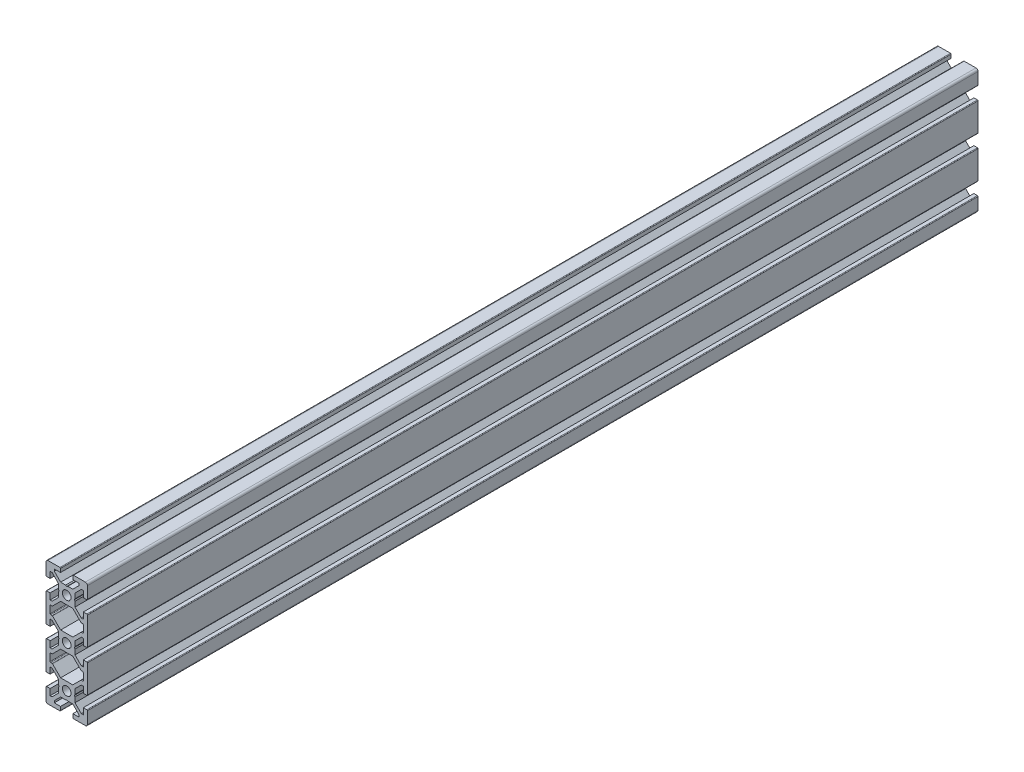
SolidWorks part; units mm, degrees
ref_plane "Front Plane" through (0, 0, 0) normal (0, 0, 1) x (1, 0, 0)
ref_plane "Top Plane" through (0, 0, 0) normal (0, 1, 0) x (1, 0, 0)
ref_plane "Right Plane" through (0, 0, 0) normal (1, 0, 0) x (0, 0, -1)
ref_plane "Plane1" through (0, 0, 0) normal (0, 0, 1) x (1, 0, 0)
sketch "Sketch1" plane through (0, 0, 0) normal (0, 0, 1) x (1, 0, 0)
  line L0 (-10, 16.7) -> (-10, 3.3)
  line L1 (-9.7, 3) -> (-8, 3)
  line L2 (-8, 3) -> (-8, 6)
  line L3 (-8, 6) -> (-7.0607, 6)
  line L4 (-7.0607, 6) -> (-4, 2.9393)
  line L5 (-4, 2.9393) -> (-4, 0.5196)
  line L6 (-4, 0.5196) -> (-3.7, 0)
  line L7 (-3.7, 0) -> (-4, -0.5196)
  line L8 (-4, -0.5196) -> (-4, -2.9394)
  line L9 (-4, -2.9394) -> (-7.0606, -6)
  line L10 (-7.0606, -6) -> (-8, -6)
  line L11 (-8, -6) -> (-8, -3)
  line L12 (-8, -3) -> (-9.7, -3)
  line L13 (-10, -3.3) -> (-10, -16.7)
  line L14 (-9.7, -17) -> (-8, -17)
  line L15 (-8, -17) -> (-8, -14)
  line L16 (-8, -14) -> (-7.0607, -14)
  line L17 (-7.0607, -14) -> (-4, -17.0607)
  line L18 (-4, -17.0607) -> (-4, -19.4804)
  line L19 (-4, -19.4804) -> (-3.7, -20)
  line L20 (-3.7, -20) -> (-4, -20.5196)
  line L21 (-4, -20.5196) -> (-4, -22.9394)
  line L22 (-4, -22.9394) -> (-7.0606, -26)
  line L23 (-7.0606, -26) -> (-8, -26)
  line L24 (-8, -26) -> (-8, -23)
  line L25 (-8, -23) -> (-9.7, -23)
  line L26 (-10, -23.3) -> (-10, -29)
  line L27 (-9, -30) -> (-3.3, -30)
  line L28 (-3, -29.7) -> (-3, -28)
  line L29 (-3, -28) -> (-6, -28)
  line L30 (-6, -28) -> (-6, -27.0607)
  line L31 (-6, -27.0607) -> (-2.9393, -24)
  line L32 (-2.9393, -24) -> (-0.5191, -24)
  line L33 (-0.5191, -24) -> (0, -23.7)
  line L34 (0, -23.7) -> (0.5186, -24)
  line L35 (0.5186, -24) -> (2.9393, -24)
  line L36 (2.9393, -24) -> (6, -27.0607)
  line L37 (6, -27.0607) -> (6, -28)
  line L38 (6, -28) -> (3, -28)
  line L39 (3, -28) -> (3, -29.7)
  line L40 (3.3, -30) -> (9, -30)
  line L41 (10, -29) -> (10, -23.3)
  line L42 (9.7, -23) -> (8, -23)
  line L43 (8, -23) -> (8, -26)
  line L44 (8, -26) -> (7.0606, -26)
  line L45 (7.0606, -26) -> (4, -22.9394)
  line L46 (4, -22.9394) -> (4, -20.5196)
  line L47 (4, -20.5196) -> (3.7, -20)
  line L48 (3.7, -20) -> (4, -19.4804)
  line L49 (4, -19.4804) -> (4, -17.0607)
  line L50 (4, -17.0607) -> (7.0607, -14)
  line L51 (7.0607, -14) -> (8, -14)
  line L52 (8, -14) -> (8, -17)
  line L53 (8, -17) -> (9.7, -17)
  line L54 (10, -16.7) -> (10, -3.3)
  line L55 (9.7, -3) -> (8, -3)
  line L56 (8, -3) -> (8, -6)
  line L57 (8, -6) -> (7.0607, -6)
  line L58 (7.0607, -6) -> (4, -2.9393)
  line L59 (4, -2.9393) -> (4, -0.5196)
  line L60 (4, -0.5196) -> (3.7, 0)
  line L61 (3.7, 0) -> (4, 0.5196)
  line L62 (4, 0.5196) -> (4, 2.9393)
  line L63 (4, 2.9393) -> (7.0607, 6)
  line L64 (7.0607, 6) -> (8, 6)
  line L65 (8, 6) -> (8, 3)
  line L66 (8, 3) -> (9.7, 3)
  line L67 (10, 3.3) -> (10, 16.7)
  line L68 (9.7, 17) -> (8, 17)
  line L69 (8, 17) -> (8, 14)
  line L70 (8, 14) -> (7.0607, 14)
  line L71 (7.0607, 14) -> (4, 17.0607)
  line L72 (4, 17.0607) -> (4, 19.4804)
  line L73 (4, 19.4804) -> (3.7, 20)
  line L74 (3.7, 20) -> (4, 20.5196)
  line L75 (4, 20.5196) -> (4, 22.9394)
  line L76 (4, 22.9394) -> (7.0606, 26)
  line L77 (7.0606, 26) -> (8, 26)
  line L78 (8, 26) -> (8, 23)
  line L79 (8, 23) -> (9.7, 23)
  line L80 (10, 23.3) -> (10, 29)
  line L81 (9, 30) -> (3.3, 30)
  line L82 (3, 29.7) -> (3, 28)
  line L83 (3, 28) -> (6, 28)
  line L84 (6, 28) -> (6, 27.0607)
  line L85 (6, 27.0607) -> (2.9393, 24)
  line L86 (2.9393, 24) -> (0.5196, 24)
  line L87 (0.5196, 24) -> (0, 23.7)
  line L88 (0, 23.7) -> (-0.5196, 24)
  line L89 (-0.5196, 24) -> (-2.9393, 24)
  line L90 (-2.9393, 24) -> (-6, 27.0607)
  line L91 (-6, 27.0607) -> (-6, 28)
  line L92 (-6, 28) -> (-3, 28)
  line L93 (-3, 28) -> (-3, 29.7)
  line L94 (-3.3, 30) -> (-9, 30)
  line L95 (-10, 29) -> (-10, 23.3)
  line L96 (-9.7, 23) -> (-8, 23)
  line L97 (-8, 23) -> (-8, 26)
  line L98 (-8, 26) -> (-7.0606, 26)
  line L99 (-7.0606, 26) -> (-4, 22.9394)
  line L100 (-4, 22.9394) -> (-4, 20.5196)
  line L101 (-4, 20.5196) -> (-3.7, 20)
  line L102 (-3.7, 20) -> (-4, 19.4804)
  line L103 (-4, 19.4804) -> (-4, 17.0607)
  line L104 (-4, 17.0607) -> (-7.0607, 14)
  line L105 (-7.0607, 14) -> (-8, 14)
  line L106 (-8, 14) -> (-8, 17)
  line L107 (-8, 17) -> (-9.7, 17)
  line L108 (-7.7, 8) -> (-7.0636, 8)
  line L109 (-6.8515, 7.9121) -> (-2.9393, 4)
  line L110 (-2.9393, 4) -> (2.9393, 4)
  line L111 (2.9393, 4) -> (6.8515, 7.9121)
  line L112 (7.0636, 8) -> (7.7, 8)
  line L113 (8, 8.3) -> (8, 11.7)
  line L114 (7.7, 12) -> (7.0636, 12)
  line L115 (6.8515, 12.0879) -> (2.9393, 16)
  line L116 (2.9393, 16) -> (-2.9393, 16)
  line L117 (-2.9393, 16) -> (-6.8515, 12.0879)
  line L118 (-7.0636, 12) -> (-7.7, 12)
  line L119 (-8, 11.7) -> (-8, 8.3)
  line L120 (-8, -8.3) -> (-8, -11.7)
  line L121 (-7.7, -12) -> (-7.0636, -12)
  line L122 (-6.8515, -12.0879) -> (-2.9394, -16)
  line L123 (-2.9394, -16) -> (2.9393, -16)
  line L124 (2.9393, -16) -> (6.8515, -12.0879)
  line L125 (7.0636, -12) -> (7.7, -12)
  line L126 (8, -11.7) -> (8, -8.3)
  line L127 (7.7, -8) -> (7.0636, -8)
  line L128 (6.8515, -7.9121) -> (2.9393, -4)
  line L129 (2.9393, -4) -> (-2.9393, -4)
  line L130 (-2.9393, -4) -> (-6.8515, -7.9121)
  line L131 (-7.0636, -8) -> (-7.7, -8)
  arc A0 (-10, 3.3) -> (-9.7, 3) centre (-9.7, 3.3) ccw
  arc A1 (-9.7, -3) -> (-10, -3.3) centre (-9.7, -3.3) ccw
  arc A2 (-10, -16.7) -> (-9.7, -17) centre (-9.7, -16.7) ccw
  arc A3 (-9.7, -23) -> (-10, -23.3) centre (-9.7, -23.3) ccw
  arc A4 (-10, -29) -> (-9, -30) centre (-9, -29) ccw
  arc A5 (-3.3, -30) -> (-3, -29.7) centre (-3.3, -29.7) ccw
  arc A6 (3, -29.7) -> (3.3, -30) centre (3.3, -29.7) ccw
  arc A7 (9, -30) -> (10, -29) centre (9, -29) ccw
  arc A8 (10, -23.3) -> (9.7, -23) centre (9.7, -23.3) ccw
  arc A9 (9.7, -17) -> (10, -16.7) centre (9.7, -16.7) ccw
  arc A10 (10, -3.3) -> (9.7, -3) centre (9.7, -3.3) ccw
  arc A11 (9.7, 3) -> (10, 3.3) centre (9.7, 3.3) ccw
  arc A12 (10, 16.7) -> (9.7, 17) centre (9.7, 16.7) ccw
  arc A13 (9.7, 23) -> (10, 23.3) centre (9.7, 23.3) ccw
  arc A14 (10, 29) -> (9, 30) centre (9, 29) ccw
  arc A15 (3.3, 30) -> (3, 29.7) centre (3.3, 29.7) ccw
  arc A16 (-3, 29.7) -> (-3.3, 30) centre (-3.3, 29.7) ccw
  arc A17 (-9, 30) -> (-10, 29) centre (-9, 29) ccw
  arc A18 (-10, 23.3) -> (-9.7, 23) centre (-9.7, 23.3) ccw
  arc A19 (-9.7, 17) -> (-10, 16.7) centre (-9.7, 16.7) ccw
  circle A20 centre (0, 20) radius 2.1
  circle A21 centre (0, 0) radius 2.1
  circle A22 centre (0, -20) radius 2.1
  arc A23 (-8, 8.3) -> (-7.7, 8) centre (-7.7, 8.3) ccw
  arc A24 (-7.0636, 8) -> (-6.8515, 7.9121) centre (-7.0636, 7.7) cw
  arc A25 (6.8515, 7.9121) -> (7.0636, 8) centre (7.0636, 7.7) cw
  arc A26 (7.7, 8) -> (8, 8.3) centre (7.7, 8.3) ccw
  arc A27 (8, 11.7) -> (7.7, 12) centre (7.7, 11.7) ccw
  arc A28 (7.0636, 12) -> (6.8515, 12.0879) centre (7.0636, 12.3) cw
  arc A29 (-6.8515, 12.0879) -> (-7.0636, 12) centre (-7.0636, 12.3) cw
  arc A30 (-7.7, 12) -> (-8, 11.7) centre (-7.7, 11.7) ccw
  arc A31 (-8, -11.7) -> (-7.7, -12) centre (-7.7, -11.7) ccw
  arc A32 (-7.0636, -12) -> (-6.8515, -12.0879) centre (-7.0636, -12.3) cw
  arc A33 (6.8515, -12.0879) -> (7.0636, -12) centre (7.0636, -12.3) cw
  arc A34 (7.7, -12) -> (8, -11.7) centre (7.7, -11.7) ccw
  arc A35 (8, -8.3) -> (7.7, -8) centre (7.7, -8.3) ccw
  arc A36 (7.0636, -8) -> (6.8515, -7.9121) centre (7.0636, -7.7) cw
  arc A37 (-6.8515, -7.9121) -> (-7.0636, -8) centre (-7.0636, -7.7) cw
  arc A38 (-7.7, -8) -> (-8, -8.3) centre (-7.7, -8.3) ccw
extrude "Boss-Extrude1" add sketch "Sketch1" against normal blind 430
